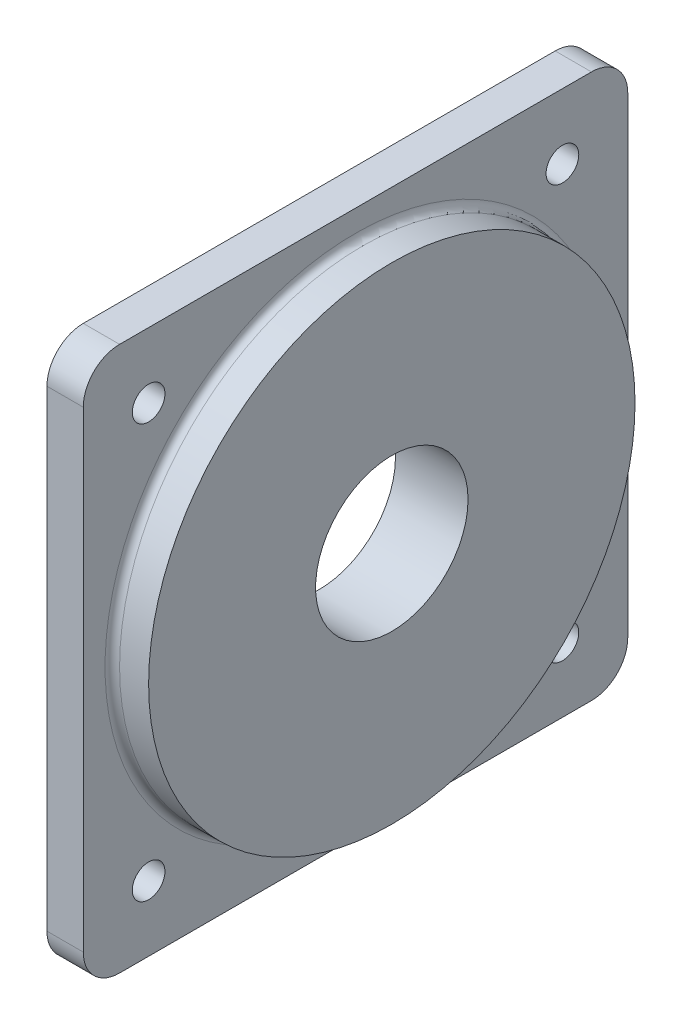
SolidWorks part; units mm, degrees
material "1060-H12"
ref_plane "Front" through (0, 0, 0) normal (0, 0, 1) x (1, 0, 0)
ref_plane "Top" through (0, 0, 0) normal (0, 1, 0) x (1, 0, 0)
ref_plane "Right" through (0, 0, 0) normal (1, 0, 0) x (0, 0, -1)
sketch "Croquis1" plane through (0, 0, 0) normal (1, 0, 0) x (0, 0, -1)
  line L1 (-75, 75) -> (75, 75)
  line L2 (-75, 75) -> (-75, -75)
  line L3 (-75, -75) -> (75, -75)
  line L4 (75, 75) -> (75, -75)
  line L5 (-75, 75) -> (75, -75) construction
  line L6 (-75, -75) -> (75, 75) construction
  point P0 (0, 0)
extrude "Saliente-Extruir1" add sketch "Croquis1" along normal blind 10
sketch "Croquis2" plane through (10, 0, 0) normal (1, 0, 0) x (0, 0, -1)
  circle A0 centre (0, 0) radius 67
  dimension "D1" = 134
extrude "Saliente-Extruir2" add sketch "Croquis2" along normal blind 10
fillet "Redondeo1" radius 10 4 edges at (5, -75, 75) (5, -75, -75) (5, 75, -75) (5, 75, 75)
fillet "Redondeo2" radius 2 1 edges at (10, 0, -67)
sketch "Croquis3" plane through (20, 0, 0) normal (1, 0, 0) x (0, 0, -1)
  line L0 (57, 0) -> (-57, 0) construction
  line L1 (57, -57) -> (-57, -57) construction
  line L2 (57, -57) -> (57, 57) construction
  line L3 (57, 57) -> (-57, 57) construction
  line L4 (-57, -57) -> (-57, 57) construction
  line L5 (57, -57) -> (-57, 57) construction
  line L6 (57, 57) -> (-57, -57) construction
  line L7 (-57, 0) -> (0, -57) construction
  line L8 (0, -57) -> (0, 57) construction
  circle A0 centre (0, 0) radius 21
  dimension "D1" = 42
  dimension "D2" = 114
extrude "Cortar-Extruir1" cut sketch "Croquis3" against normal through all
hole_wizard "Taladro de margen para M81" positions "Croquis4" profile "Croquis5" hole size "M8" standard "Ansi Metric" end condition through all
sketch "Croquis4" plane through (10, -7.4173, 252.7608) normal (1, 0, 0) x (0, 0, -1)
  line L0 (252.7608, 7.4173) -> (252.7608, 64.4173) construction
  point P0 (195.7608, 64.4173)
  point P2 (309.7608, 64.4173)
  point P10 (0, 0)
  point P11 (0, 0)
sketch "Croquis5" plane through (10, 57, 57) normal (0, 1, 0) x (0, 0, -1)
  line L0 (0, 0) -> (0, 10)
  line L1 (0, 10) -> (4.5, 10)
  line L2 (4.5, 10) -> (4.5, 0)
  line L3 (4.5, 0) -> (0, 0)
  line L4 (0, -6.35) -> (0, 107.95) construction
  dimension "Diámetro de taladro hasta el siguiente" = 9
  dimension "Profundidad de taladro hasta el siguiente" = 10
hole_wizard "Taladro de margen para M82" positions "Croquis6" profile "Croquis7" hole size "M8" standard "Ansi Metric" end condition through all
sketch "Croquis6" plane through (10, -7.4173, 252.7608) normal (1, 0, 0) x (0, 0, -1)
  point P0 (309.7608, -49.5827)
  point P2 (195.7608, -49.5827)
  point P6 (309.7608, -49.5827)
sketch "Croquis7" plane through (10, -57, -57) normal (0, 1, 0) x (0, 0, -1)
  line L0 (0, 0) -> (0, 10)
  line L1 (0, 10) -> (4.5, 10)
  line L2 (4.5, 10) -> (4.5, 0)
  line L3 (4.5, 0) -> (0, 0)
  line L4 (0, -6.35) -> (0, 107.95) construction
  dimension "Diámetro de taladro hasta el siguiente" = 9
  dimension "Profundidad de taladro hasta el siguiente" = 10
